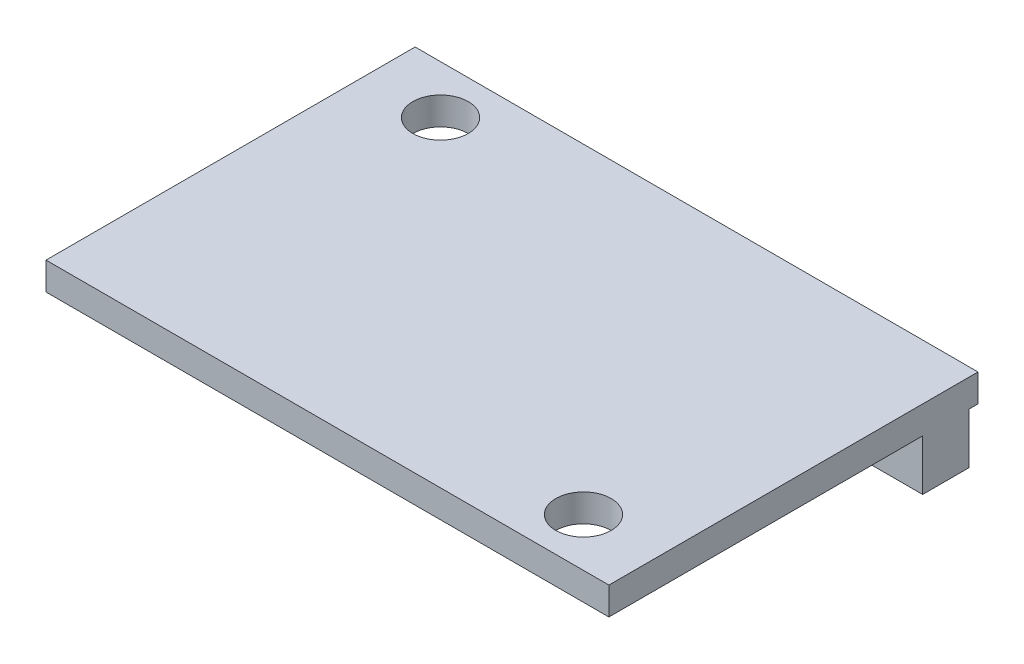
SolidWorks part; units mm, degrees
ref_plane "Alzado" through (0, 0, 0) normal (0, 0, 1) x (1, 0, 0)
ref_plane "Planta" through (0, 0, 0) normal (0, 1, 0) x (1, 0, 0)
ref_plane "Vista lateral" through (0, 0, 0) normal (1, 0, 0) x (0, 0, -1)
sketch "Croquis1" plane through (0, 0, 0) normal (0, 1, 0) x (1, 0, 0)
  line L1 (-15.25, -10) -> (15.25, -10)
  line L2 (-15.25, -10) -> (-15.25, 10)
  line L3 (-15.25, 10) -> (15.25, 10)
  line L4 (15.25, -10) -> (15.25, 10)
  line L5 (-15.25, -10) -> (15.25, 10) construction
  line L6 (-15.25, 10) -> (15.25, -10) construction
  circle A0 centre (-11.25, 7.377) radius 1.5
  circle A1 centre (11.25, -7.377) radius 1.5
  point P0 (0, 0)
  point P10 (-12.9337, 8.4811)
  point P11 (11.7365, -7.6961)
  point P12 (-11.0907, 7.2726)
  dimension "D3" = 3
  dimension "D5" = 4
  dimension "D1" = 30.5
  dimension "D2" = 20
  dimension "D4" = 4
extrude "Saliente-Extruir1" add sketch "Croquis1" along normal blind 1.5
sketch "Croquis2" plane through (0, 0, 0) normal (0, -1, 0) x (1, 0, 0)
  line L0 (15.25, -10) -> (-15.25, -10) construction
  line L1 (-6.75, -7) -> (15.25, -7)
  line L2 (-6.75, -7) -> (-6.75, -9.5)
  line L3 (-6.75, -9.5) -> (15.25, -9.5)
  line L4 (15.25, -7) -> (15.25, -9.5)
  line L5 (15.25, 10) -> (15.25, -10) construction
  dimension "D1" = 2.5
  dimension "D2" = 0.5
  dimension "D3" = 22
extrude "Saliente-Extruir2" add sketch "Croquis2" along normal blind 2.75
